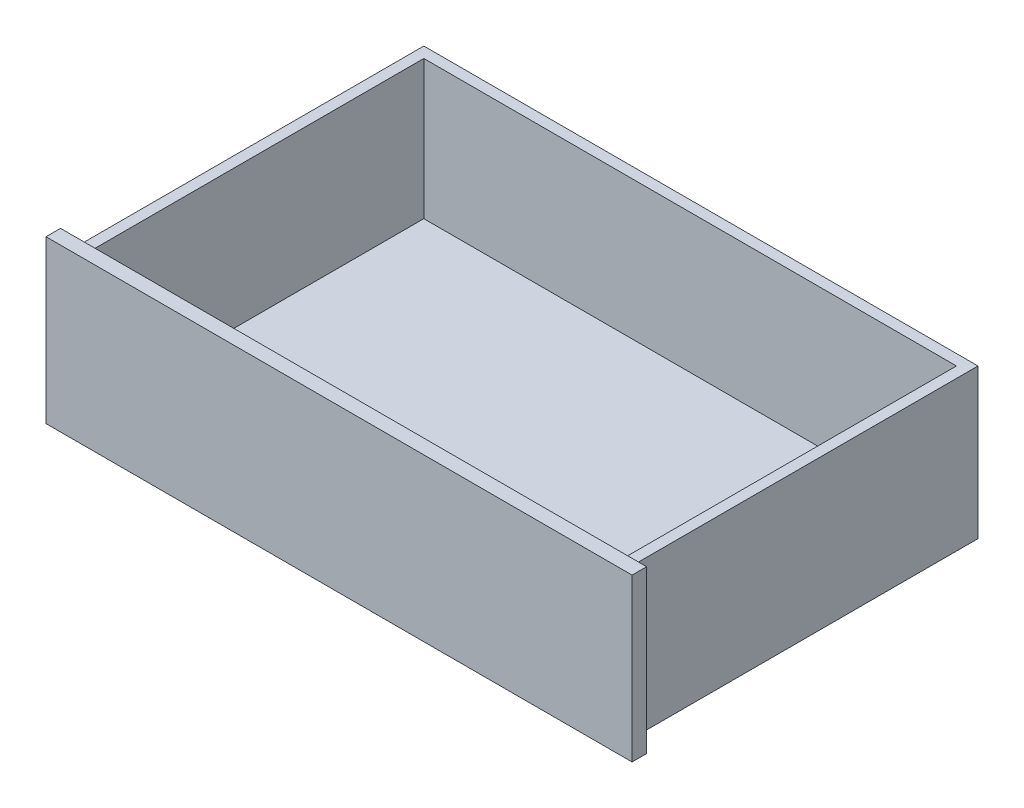
SolidWorks part; units mm, degrees
material "Maple"
ref_plane "Front Plane" through (0, 0, 0) normal (0, 0, 1) x (1, 0, 0)
ref_plane "Top Plane" through (0, 0, 0) normal (0, 1, 0) x (1, 0, 0)
ref_plane "Right Plane" through (0, 0, 0) normal (1, 0, 0) x (0, 0, -1)
sketch "Sketch1" plane through (0, 0, 0) normal (0, 1, 0) x (1, 0, 0)
  line L1 (-315, -200) -> (315, -200)
  line L2 (-315, -200) -> (-315, 200)
  line L3 (-315, 200) -> (315, 200)
  line L4 (315, -200) -> (315, 200)
  line L5 (-315, -200) -> (315, 200) construction
  line L6 (-315, 200) -> (315, -200) construction
  point P0 (0, 0)
  dimension "D1" = 630
  dimension "D2" = 400
extrude "Extrusion" add sketch "Sketch1" along normal blind 170
shell "Drawer's interior" thickness 12.2428
sketch "Sketch2" plane through (0, 0, 200) normal (0, 0, 1) x (1, 0, 0)
  line L0 (-315, 0) -> (315, 0) construction
  line L1 (-351.5, -5) -> (351.5, -5)
  line L2 (-351.5, -5) -> (-351.5, 175)
  line L3 (-351.5, 175) -> (351.5, 175)
  line L4 (351.5, -5) -> (351.5, 175)
  line L5 (-351.5, -5) -> (351.5, 175) construction
  line L6 (-351.5, 175) -> (351.5, -5) construction
  line L7 (315, 170) -> (315, 0) construction
  point P0 (0, 85)
  point P8 (0, 0)
  point P14 (315, 85)
  dimension "D1" = 703
  dimension "D2" = 180
extrude "Boss-Extrude2" [suppressed] add sketch "Sketch2" along normal blind 17 contours L4 L3 L2 L1
sketch "Sketch3" plane through (0, 0, 200) normal (0, 0, 1) x (1, 0, 0)
  line L0 (315, 170) -> (315, 0) construction
  line L1 (-328, 184) -> (338.2428, 184)
  line L2 (-328, 184) -> (-328, 0)
  line L4 (338.2428, 184) -> (338.2428, 0)
  line L5 (-315, 170) -> (-315, 0) construction
  line L6 (-315, 170) -> (315, 170) construction
  line L8 (-328, 0) -> (338.2428, 0)
  line L9 (-315, 0) -> (315, 0) construction
  dimension "D1" = 23.2428
  dimension "D2" = 13
  dimension "D3" = 14
  dimension "D4" = 0
extrude "Boss-Extrude3" add sketch "Sketch3" along normal blind 16.5
equation "\"D1@Drawer's interior\"=\"Drawer_side_tickness@Drawer Assembly Narrow.Assembly\""
equation "\"D2@Sketch1\"=\"Drawer_length@Drawer Assembly Narrow.Assembly\""
equation "\"D3@Sketch3\"=\"Drawer_top_clearance@Drawer Assembly Narrow.Assembly\""
equation "\"D1@Sketch3\"=\"Drawer­_to_sidewall@Drawer Assembly Narrow.Assembly\"+\"Drawer_side_tickness@Drawer Assembly Narrow.Assembly\""
